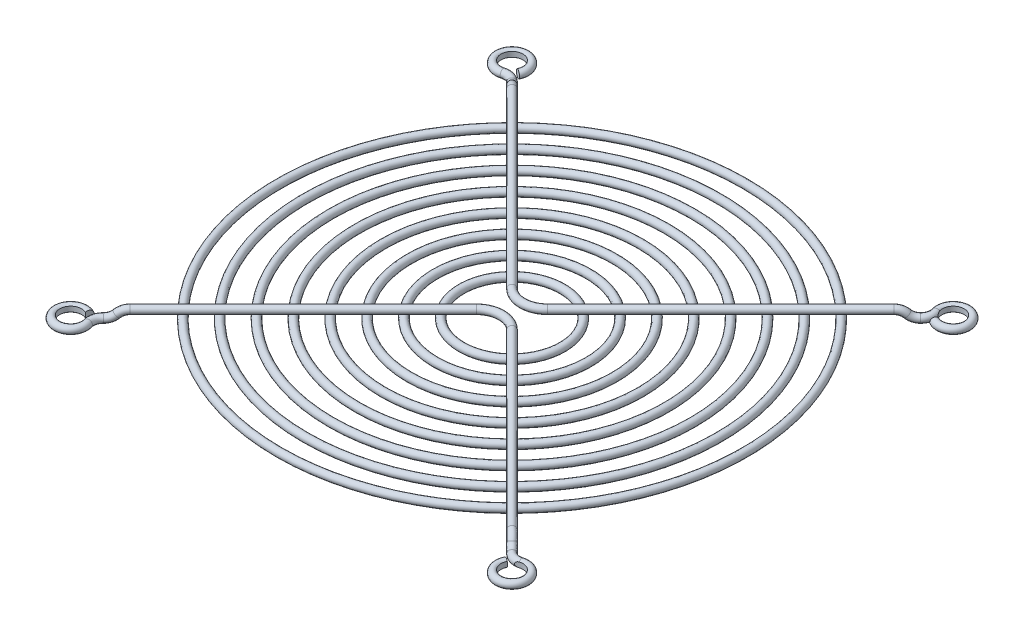
SolidWorks part; units mm, degrees
ref_plane "Спереди" through (0, 0, 0) normal (0, 0, 1) x (1, 0, 0)
ref_plane "Сверху" through (0, 0, 0) normal (0, 1, 0) x (1, 0, 0)
ref_plane "Справа" through (0, 0, 0) normal (1, 0, 0) x (0, 0, -1)
sketch "Эскиз1" plane through (0, 0, 0) normal (1, 0, 0) x (0, 0, -1)
  line L0 (0, -1.8) -> (96.5366, -1.8) construction
  line L1 (0, -1.8) -> (0, -9.2394) construction
  circle A0 centre (12, -1.8) radius 0.9
  circle A1 centre (18.2, -1.8) radius 0.9
  circle A3 centre (24.4, -1.8) radius 0.9
  circle A4 centre (30.6, -1.8) radius 0.9
  circle A5 centre (36.8, -1.8) radius 0.9
  circle A6 centre (43, -1.8) radius 0.9
  circle A7 centre (49.2, -1.8) radius 0.9
  circle A8 centre (55.4, -1.8) radius 0.9
  dimension "D2" = 1.8
  dimension "D1" = 12
  dimension "D4" = 1.8
  dimension "D3" = 8
revolve "Повернуть1" add sketch "Эскиз1" angle 360 about L1
sketch "Эскиз2" plane through (0, 0, 0) normal (0, 1, 0) x (1, 0, 0)
  line L0 (-4.2426, 4.2426) -> (-45.4289, 45.4289)
  line L1 (4.2426, 4.2426) -> (45.4289, 45.4289)
  line L2 (4.2426, -4.2426) -> (45.4289, -45.4289)
  line L3 (-4.2426, -4.2426) -> (-45.4289, -45.4289)
  line L4 (0, 0) -> (65.0166, 0) construction
  line L5 (45.4289, 45.4289) -> (52.5, 52.5) construction
  circle A0 centre (0, 0) radius 6 construction
  arc A1 (-4.2426, -4.2426) -> (4.2426, -4.2426) centre (0, -8.4853) cw
  arc A2 (4.2426, 4.2426) -> (-4.2426, 4.2426) centre (0, 8.4853) cw
  point P14 (52.5, 52.5)
  dimension "D2" = 12
  dimension "D1" = 45
  dimension "D3" = 10
  dimension "D4" = 105
  dimension "D5" = 64.2462
ref_plane "Плоскость3" through (0, 0, 0) normal (0.7071, 0, 0.7071) x (0.7071, 0, -0.7071)
sketch "Эскиз3" plane through (0, 0, 0) normal (0.7071, 0, 0.7071) x (0.7071, 0, -0.7071)
  line L0 (6, 0) -> (64.2462, 0) construction
  line L1 (87.0459, -1.8) -> (0, -1.8) construction
  arc A0 (64.2462, 0) -> (66.4962, -0.9) centre (64.2462, -3.2625) cw
  arc A1 (66.4962, -0.9) -> (68.7462, -1.8) centre (68.7462, 1.4625) ccw
  dimension "D1" = 2.25
  dimension "D2" = 1.8
ref_plane "Плоскость4" through (0, -1.8, 0) normal (0, 1, 0) x (1, 0, 0)
sketch "Эскиз4" plane through (0, -1.8, 0) normal (0, 1, 0) x (1, 0, 0)
  line L0 (61.5507, 61.5507) -> (0, 0) construction
  line L1 (45.4289, 45.4289) -> (52.5, 52.5) construction
  arc A0 (48.6109, 48.6109) -> (49.3677, 51.5787) centre (46.4896, 50.7322) ccw
  arc A1 (51.0094, 49.5952) -> (49.3677, 51.5787) centre (52.5, 52.5) ccw
  point P3 (0, 0)
  point P9 (53.0019, 53.0019)
  point P10 (53.0019, 53.0019)
  point P11 (0, 0)
  point P12 (52.9907, 53.0378)
  point P14 (0, 0)
  point P16 (52.674, 52.6362)
  dimension "D1" = 3.265
  dimension "D2" = 3
  dimension "D3" = 1
sweep "По траектории1" add path "Эскиз2" circular profile diameter 1.8 parameters "D3"=1.8
mirror "Зеркальное отражение6" about plane through (0, 0, 0) normal (0, 0, 1) of bodies 108
sweep "По траектории2" add path "Эскиз4" circular profile diameter 1.8 parameters "D3"=1.8
sweep "По траектории3" add path "Эскиз3" circular profile diameter 1.8 parameters "D3"=1.8
sketch "Эскиз50" plane through (0, 0, 0) normal (0, 1, 0) x (1, 0, 0)
  circle A0 centre (52.5, 52.5) radius 2.6
  dimension "D1" = 5.2
extrude "Вырез-Вытянуть1" cut sketch "Эскиз50" against normal through all both and the other way through all
pattern_circular "Круговой массив5" count 4 over 360 about axis through (0, 0, 0) along (0, 1, 0) of "По траектории3", "По траектории2", "Вырез-Вытянуть1"
sketch "Эскиз46" plane through (0, 0, 0) normal (0, 1, 0) x (1, 0, 0)
  line L1 (60, 60) -> (-60, 60) construction
  line L2 (60, 60) -> (60, -60) construction
  line L3 (60, -60) -> (-60, -60) construction
  line L4 (-60, 60) -> (-60, -60) construction
  line L5 (60, 60) -> (-60, -60) construction
  line L6 (60, -60) -> (-60, 60) construction
  circle A0 centre (0, 0) radius 58 construction
  point P0 (0, 0)
  dimension "D2" = 116
  dimension "D1" = 120
